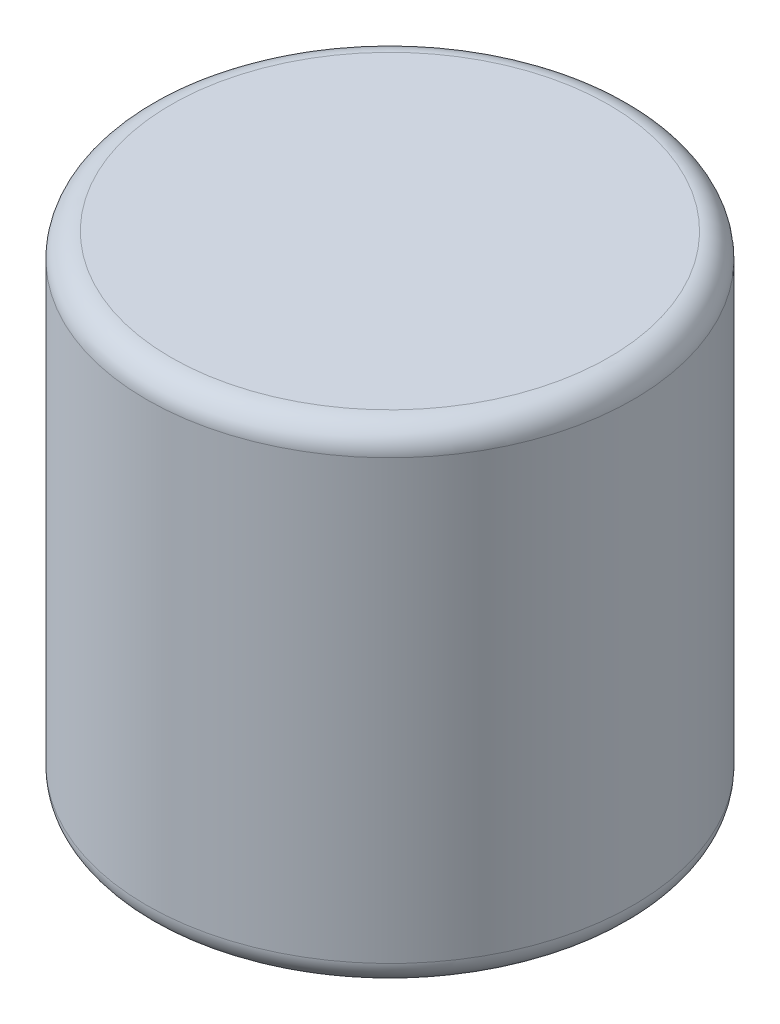
SolidWorks part; units mm, degrees
other "magnet"
ref_plane "Front Plane" through (0, 0, 0) normal (0, 0, 1) x (1, 0, 0)
ref_plane "Top Plane" through (0, 0, 0) normal (0, 1, 0) x (1, 0, 0)
ref_plane "Right Plane" through (0, 0, 0) normal (1, 0, 0) x (0, 0, -1)
sketch "Sketch1" plane through (0, 0, 0) normal (0, 1, 0) x (1, 0, 0)
  circle A0 centre (0, 0) radius 1
  dimension "D1" = 2
extrude "Boss-Extrude1" add sketch "Sketch1" along normal blind 2
fillet "Fillet1" radius 0.1 2 edges at (0, 0, 1) (0, 2, 1)
